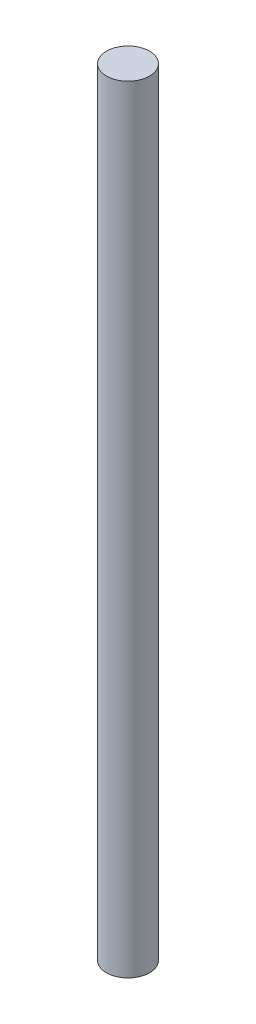
SolidWorks part; units mm, degrees
ref_plane "前视基准面" through (0, 0, 0) normal (0, 0, 1) x (1, 0, 0)
ref_plane "上视基准面" through (0, 0, 0) normal (0, 1, 0) x (1, 0, 0)
ref_plane "右视基准面" through (0, 0, 0) normal (1, 0, 0) x (0, 0, -1)
sketch "草图1" plane through (0, 0, 0) normal (0, 1, 0) x (1, 0, 0)
  circle A0 centre (0, 0) radius 10
  dimension "D1" = 20
extrude "凸台-拉伸1" add sketch "草图1" along normal mid plane 360
